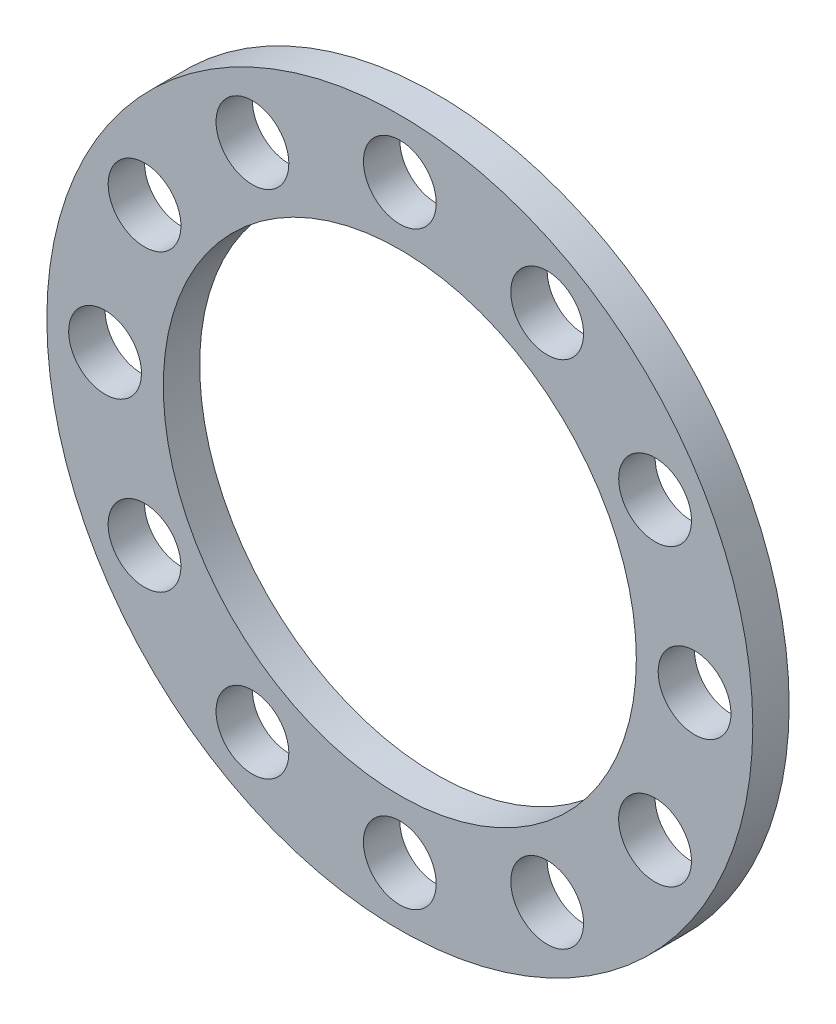
SolidWorks part; units mm, degrees
ref_plane "Front Plane" through (0, 0, 0) normal (0, 0, 1) x (1, 0, 0)
ref_plane "Top Plane" through (0, 0, 0) normal (0, 1, 0) x (1, 0, 0)
ref_plane "Right Plane" through (0, 0, 0) normal (1, 0, 0) x (0, 0, -1)
sketch "Sketch1" plane through (0, 0, 0) normal (0, 0, 1) x (1, 0, 0)
  line L0 (-48.5, 0) -> (48.5, 0) construction
  circle A0 centre (0, 0) radius 48.5
  circle A1 centre (0, 0) radius 32.5
  dimension "D1" = 97
  dimension "D2" = 65
extrude "Body" add sketch "Sketch1" along normal blind 5
sketch "Sketch2" plane through (0, 0, 5) normal (0, 0, 1) x (1, 0, 0)
  line L0 (0, 0) -> (0, 48.5) construction
  circle A0 centre (0, 0) radius 48.5 construction
  circle A1 centre (0, 40.5) radius 5
  dimension "D1" = 10
  dimension "D2" = 40.5
extrude "Bolt Hole" cut sketch "Sketch2" against normal through all
pattern_circular "CirPattern1" count 12 over 360 about axis through (0, 0, 0) along (0, 0, 1) of "Bolt Hole"
equation "\"outer_diameter\"= 97.0mm"
equation "\"inner_diameter\"= 65.0mm"
equation "\"spacer_thickness\"= 4.0mm"
equation "\"bolt_diameter\"= 10.0mm"
equation "\"bolt_placement_radius\"= 40.5mm"
equation "\"num_bolts\"= 12.0"
equation "\"D1@Sketch1\"=\"outer_diameter\""
equation "\"D2@Sketch1\"=\"inner_diameter\""
equation "\"D1@Body\" = \"spacer_thickness\""
equation "\"D1@Sketch2\"=\"bolt_diameter\""
equation "\"D2@Sketch2\"=\"bolt_placement_radius\""
equation "\"D1@CirPattern1\"=\"num_bolts\""
